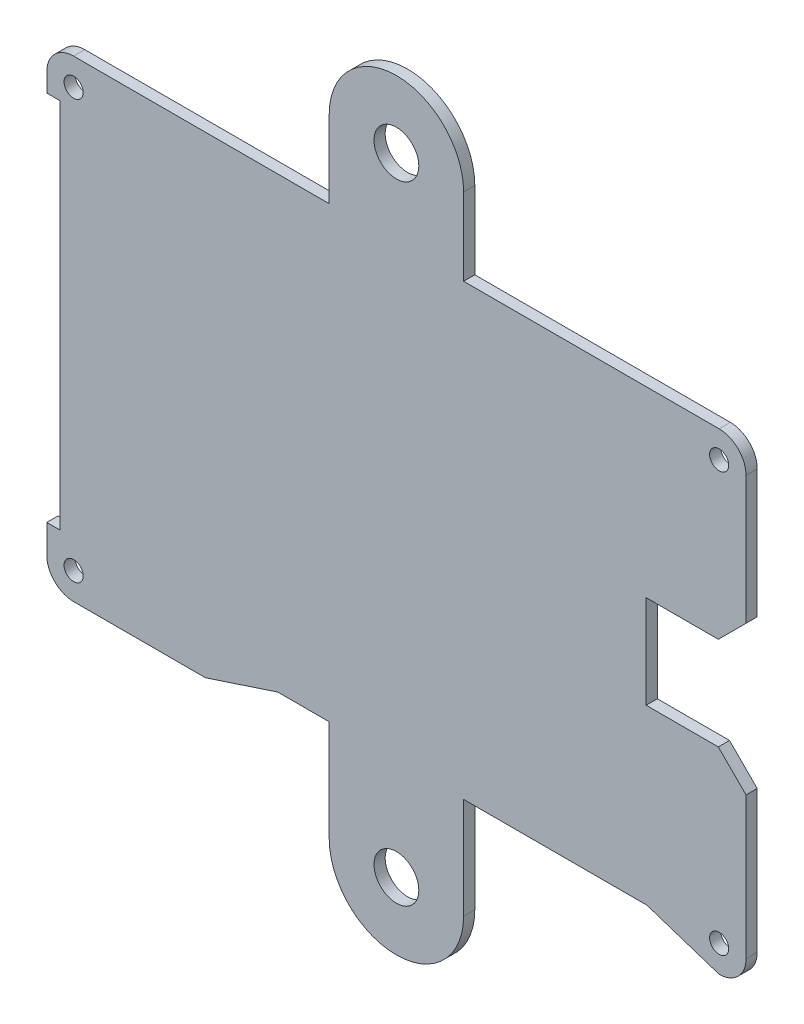
SolidWorks part; units mm, degrees
ref_plane "Front Plane" through (0, 0, 0) normal (0, 0, 1) x (1, 0, 0)
ref_plane "Top Plane" through (0, 0, 0) normal (0, 1, 0) x (1, 0, 0)
ref_plane "Right Plane" through (0, 0, 0) normal (1, 0, 0) x (0, 0, -1)
sketch "Sketch1" plane through (0, 0, 0) normal (0, 0, 1) x (1, 0, 0)
  line L0 (-301.9473, 111.7465) -> (-305.8779, 115.6771) construction
  line L1 (-305.8779, 115.6771) -> (-316.1078, 115.6771) construction
  line L2 (-316.1078, 115.6771) -> (-316.1078, 128.8851) construction
  line L3 (-316.1078, 128.8851) -> (-305.8779, 128.8851) construction
  line L4 (-305.8779, 128.8851) -> (-301.9473, 132.8157) construction
  line L5 (-301.9473, 132.8157) -> (-301.9473, 150.9704) construction
  line L6 (-305.7573, 154.7804) -> (-397.2471, 154.7804) construction
  line L7 (-401.0571, 150.9566) -> (-401.0571, 148.341) construction
  line L8 (-401.0571, 148.341) -> (-399.1521, 148.341) construction
  line L9 (-399.1521, 148.341) -> (-399.1521, 95.6449) construction
  line L10 (-399.1521, 95.6449) -> (-401.0571, 95.6449) construction
  line L11 (-401.0571, 95.6449) -> (-401.0571, 91.6593) construction
  line L12 (-397.2472, 87.8217) -> (-378.5565, 87.8217) construction
  line L13 (-378.5565, 87.8217) -> (-368.3165, 91.1883) construction
  line L14 (-368.3165, 91.1883) -> (-315.9973, 91.1883) construction
  line L15 (-315.9973, 91.1883) -> (-305.7573, 87.8217) construction
  line L16 (-301.9473, 91.6317) -> (-301.9473, 111.7465) construction
  line L17 (-301.9473, 111.7465) -> (-305.8779, 115.6771)
  line L18 (-305.8779, 115.6771) -> (-316.1078, 115.6771)
  line L19 (-316.1078, 115.6771) -> (-316.1078, 128.8851)
  line L20 (-316.1078, 128.8851) -> (-305.8779, 128.8851)
  line L21 (-305.8779, 128.8851) -> (-301.9473, 132.8157)
  line L22 (-301.9473, 132.8157) -> (-301.9473, 150.9704)
  line L23 (-305.7573, 154.7804) -> (-397.2471, 154.7804)
  line L24 (-401.0571, 150.9566) -> (-401.0571, 148.341)
  line L25 (-401.0571, 148.341) -> (-399.1521, 148.341)
  line L26 (-399.1521, 148.341) -> (-399.1521, 95.6449)
  line L27 (-399.1521, 95.6449) -> (-401.0571, 95.6449)
  line L28 (-401.0571, 95.6449) -> (-401.0571, 91.6593)
  line L29 (-397.2472, 87.8217) -> (-378.5565, 87.8217)
  line L30 (-378.5565, 87.8217) -> (-368.3165, 91.1883)
  line L31 (-368.3165, 91.1883) -> (-315.9973, 91.1883)
  line L32 (-315.9973, 91.1883) -> (-305.7573, 87.8217)
  line L33 (-301.9473, 91.6317) -> (-301.9473, 111.7465)
  circle A0 centre (-305.7573, 91.6317) radius 1.3559 construction
  circle A1 centre (-305.7573, 150.9704) radius 1.3559 construction
  circle A2 centre (-397.2471, 150.9704) radius 1.3559 construction
  circle A3 centre (-397.2472, 91.6317) radius 1.3559 construction
  circle A4 centre (-305.7573, 91.6317) radius 1.3559
  circle A5 centre (-305.7573, 150.9704) radius 1.3559
  circle A6 centre (-397.2471, 150.9704) radius 1.3559
  circle A7 centre (-397.2472, 91.6317) radius 1.3559
  arc A8 (-301.9473, 150.9704) -> (-305.7573, 154.7804) centre (-305.7573, 150.9704) ccw construction
  arc A9 (-397.2471, 154.7804) -> (-401.0571, 150.9566) centre (-397.2471, 150.9704) ccw construction
  arc A10 (-401.0571, 91.6593) -> (-397.2472, 87.8217) centre (-397.2472, 91.6317) ccw construction
  arc A11 (-305.7573, 87.8217) -> (-301.9473, 91.6317) centre (-305.7573, 91.6317) ccw construction
  arc A12 (-301.9473, 150.9704) -> (-305.7573, 154.7804) centre (-305.7573, 150.9704) ccw
  arc A13 (-397.2471, 154.7804) -> (-401.0571, 150.9566) centre (-397.2471, 150.9704) ccw
  arc A14 (-401.0571, 91.6593) -> (-397.2472, 87.8217) centre (-397.2472, 91.6317) ccw
  arc A15 (-305.7573, 87.8217) -> (-301.9473, 91.6317) centre (-305.7573, 91.6317) ccw
extrude "Boss-Extrude1" add sketch "Sketch1" along normal blind 1.5875
sketch "Sketch2" plane through (0, 0, 1.5875) normal (0, 0, 1) x (1, 0, 0)
  line L0 (-351.5022, 121.301) -> (-351.5022, 165.751) construction
  line L1 (-301.9473, 150.9704) -> (-301.9473, 91.6317) construction
  line L2 (-401.0571, 121.301) -> (-301.9473, 121.301) construction
  line L3 (-351.5022, 76.8511) -> (-351.5022, 165.751) construction
  line L4 (-361.0272, 76.8511) -> (-361.0272, 165.751)
  line L5 (-341.9772, 76.8511) -> (-341.9772, 165.751)
  line L6 (-361.0272, 154.7804) -> (-341.9772, 154.7804)
  line L7 (-305.7573, 154.7804) -> (-397.2471, 154.7804) construction
  line L8 (-361.0272, 91.6317) -> (-341.9772, 91.6317)
  circle A0 centre (-351.5022, 165.751) radius 3.175
  arc A1 (-361.0272, 76.8511) -> (-341.9772, 76.8511) centre (-351.5022, 76.8511) ccw
  arc A2 (-341.9772, 165.751) -> (-361.0272, 165.751) centre (-351.5022, 165.751) ccw
  circle A3 centre (-351.5022, 76.8511) radius 3.175
  point P13 (-351.5022, 121.301)
  line M11 (-305.7573, 154.7804) -> (-397.2471, 154.7804)
  line M21 (-368.3165, 91.1883) -> (-315.9973, 91.1883)
  dimension "D1" = 6.35
  dimension "D2" = 44.45
  dimension "D3" = 19.05
extrude "Boss-Extrude2" add sketch "Sketch2" against normal blind 1.5875 contours L5 A2 L4 A0 M11 | L4 A1 L5 A3 M21
